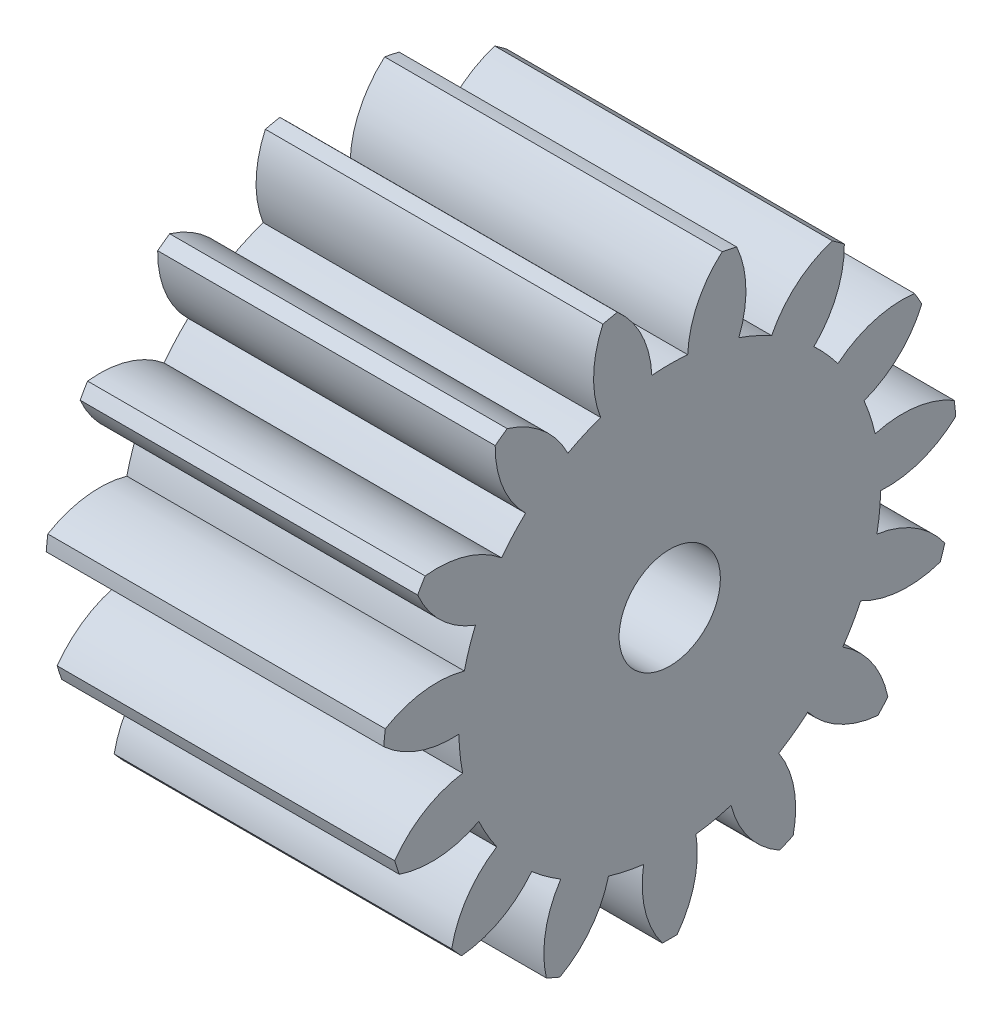
SolidWorks part; units mm, degrees
ref_plane "Plane1" through (0, 0, 0) normal (0, 0, 1) x (1, 0, 0)
ref_plane "Plane2" through (0, 0, 0) normal (0, 1, 0) x (1, 0, 0)
ref_plane "Plane3" through (0, 0, 0) normal (1, 0, 0) x (0, 0, -1)
sketch "HoldingSke" plane through (0, 0, 0) normal (0, 1, 0) x (1, 0, 0)
  line L0 (0, 0) -> (0.9659, -0.2588)
  line L1 (-15, 0) -> (100, 0) construction
  line L2 (0, 0) -> (-2.1039, 2.3779)
  line L3 (0, 0) -> (-11.863, 4.5341)
  line L4 (0, 0) -> (8.3417, 2.2352)
  line L5 (0, 0) -> (-46.8476, -17.4728)
  line L6 (0, 0) -> (-9.9476, -6.7116)
  line L7 (-2.1039, 2.3779) -> (8.6586, 51.2059)
  line L8 (-76.2, 54.61) -> (-76.1, 54.61)
  line L9 (-71.009, 38.7566) -> (-53.1078, 45.2721)
  line L10 (-76.2, 71.12) -> (104.1128, 71.12)
  line L11 (0, 0) -> (-12, 0)
  line L12 (-76.2, 101.6) -> (-76.162, 101.6)
  line L13 (24.9733, 27.94) -> (52.9518, 28.4284)
  line L14 (24.9733, 27.94) -> (24.9743, 27.94)
  line L15 (24.9733, 27.94) -> (100.4006, 29.5858)
  line L16 (-63.627, -1) -> (-12.827, -1)
  circle A0 centre (0, 0) radius 0.4
  circle A1 centre (0, 0) radius 6.249
  circle A2 centre (0, 0) radius 37.5
  circle A3 centre (0, 0) radius 0.4
  dimension "MHD" = 12.498
  dimension "Hub_dia" = 75
  dimension "Bore" = 0.8
  dimension "MBD" = 0.8
  dimension "Num_teeth" = 15
  dimension "Pitch" = 1
  dimension "Overall_len" = 50
  dimension "Show_teeth" = 15
  dimension "Thickness" = 12
  dimension "OAL" = 50.0001
  dimension "T_dim" = 0.1
  dimension "Ap" = 20
  dimension "H" = 19.05
  dimension "Pitch_radius" = 180.3128
  dimension "Width" = 12
  dimension "Backlash" = 0.038
  dimension "Addendum_fac" = 1
  dimension "Dedendum_fac" = 1.25
  dimension "Clearance_fac" = 0.25
  dimension "Dedendum_add" = 0.001
  dimension "Module" = 1
sketch "BasProSke" plane through (0, 0, 0) normal (0, 1, 0) x (1, 0, 0)
  line L0 (-10, 0) -> (60, 0) construction
  line L1 (0, 0) -> (0, 8.5)
  line L2 (0, 0) -> (10, 0)
  line L3 (10, 0) -> (10, 8.5)
  line L4 (10, 8.5) -> (0, 8.5)
  dimension "Thickness" = 10
  dimension "Diameter" = 17
revolve "Base-Revolve" add sketch "BasProSke" angle 360 about L0
sketch "TooCutSke" plane through (0, 0, 0) normal (1, 0, 0) x (0, 0, -1)
  line L1 (0, 0) -> (0, 107) construction
  line L2 (0, 0) -> (-0.8504, 7.4516) construction
  line L3 (0, 0) -> (-3.1044, 14.6049) construction
  line L4 (-0.8504, 7.4516) -> (-1.5522, 7.3025) construction
  arc A0 (0.5316, 6.2263) -> (-0.5316, 6.2263) centre (0, 0) ccw
  arc A1 (1.5766, 8.3784) -> (-1.5766, 8.3784) centre (0, 0) ccw
  circle A2 centre (0, 0) radius 7.5 construction
  circle A3 centre (0, 0) radius 7.0477 construction
  arc A4 (-0.5316, 6.2263) -> (-1.5766, 8.3784) centre (-3.5289, 6.1005) ccw
  arc A5 (1.5766, 8.3784) -> (0.5316, 6.2263) centre (3.5289, 6.1005) ccw
  dimension "Root_dia" = 12.498
  dimension "Overcut_dia" = 17.0508
  dimension "Pitch_dia" = 15
  dimension "Base_dia" = 14.0954
  dimension "Flank_rad" = 3
  dimension "Half_ang" = 12
  dimension "Half_CT" = 0.7175
extrude "ToothCut" cut sketch "TooCutSke" along normal through all
fillet "Breaks" [suppressed] radius 0.02
fillet "RootFillets" [suppressed] radius 0.251
pattern_circular "TeethCuts" count 15 every 24 about axis through (-10, 0, 0) along (1, 0, 0) of "ToothCut", "RootFillets", "Breaks"
sketch "HubNeaOneSke" plane through (0, 0, 0) normal (-1, 0, 0) x (0, 0, 1)
  circle A0 centre (0, 0) radius 6.249
  dimension "Diameter" = 12.498
extrude "HubNearOne" [suppressed] add sketch "HubNeaOneSke" along normal blind 40.0001
sketch "HubNeaBotSke" plane through (0, 0, 0) normal (-1, 0, 0) x (0, 0, 1)
  circle A0 centre (0, 0) radius 6.249
  dimension "Diameter" = 12.498
extrude "HubNearBoth" [suppressed] add sketch "HubNeaBotSke" along normal blind 20
ref_plane "FarPln" through (10, 0, 0) normal (1, 0, 0) x (0, 0, -1)
sketch "HubFarSke" plane through (10, 0, 0) normal (1, 0, 0) x (0, 0, -1)
  circle A0 centre (0, 0) radius 6.249
  dimension "Diameter" = 12.498
extrude "HubFar" [suppressed] add sketch "HubFarSke" along normal blind 20
sketch "BorSke" plane through (0, 0, 0) normal (1, 0, 0) x (0, 0, -1)
  circle A0 centre (0, 0) radius 0.4
  dimension "Diameter" = 0.8
extrude "Bore" cut sketch "BorSke" along normal mid plane 100.0001
sketch "KeySke" plane through (0, 0, 0) normal (1, 0, 0) x (0, 0, -1)
  line L0 (-0.05, 0) -> (-0.05, 0.5)
  line L1 (-0.05, 0.5) -> (0.05, 0.5)
  line L2 (0.05, 0.5) -> (0.05, 0)
  line L3 (0, 0) -> (0, 34) construction
  line L4 (-0.05, 0) -> (0.05, 0)
  dimension "Offset" = 0.5
  dimension "Width" = 0.1
extrude "Keyway" [suppressed] cut sketch "KeySke" along normal mid plane 100.0001
pattern_circular "Keyway2" [suppressed] count 2 every 90 about axis through (-10, 0, 0) along (1, 0, 0)
sketch "Sketch1" plane through (10, 0, 0) normal (1, 0, 0) x (0, 0, -1)
  circle A0 centre (0, 0) radius 1.5
  dimension "D1" = 3
extrude "Cut-Extrude1" cut sketch "Sketch1" against normal up to next
sketch "Sketch2" plane through (10, 0, 0) normal (1, 0, 0) x (0, 0, -1)
  circle A0 centre (0, 0) radius 7.3745 construction
equation "' \"Module@HoldingSke\" = 6.35"
equation "' \"Num_teeth@HoldingSke\" = 12"
equation "' \"Ap@HoldingSke\" =  20"
equation "' \"Ap@HoldingSke\" = 20"
equation "' \"Width@HoldingSke\" = 0.5 * 25.4"
equation "' \"Hub_dia@HoldingSke\"= 1 * 25.4"
equation "' \"Hub_dia@HoldingSke\" = 1 * 25.4"
equation "' \"Overall_len@HoldingSke\" = 1.0 * 25.4"
equation "' \"Bore@HoldingSke\" = 0.75 * 25.4"
equation "' \"T_dim@HoldingSke\" = 0.1 * 25.4"
equation "' \"Width@KeySke\" = 0.25 * 25.4"
equation "' \"Show_teeth@HoldingSke\" = 13"
equation "' \"Backlash@HoldingSke\" = 0.009 * 25.4"
equation "' \"Addendum_fac@HoldingSke\" = 1.0"
equation "' \"Dedendum_fac@HoldingSke\" = 1.25"
equation "' \"Dedendum_add@HoldingSke\" = 0.00005 * 25.4"
equation "' \"Clearance_fac@HoldingSke\" = 0.25"
equation "\"Pitch@HoldingSke\" = 1 / \"Module@HoldingSke\""
equation "\"Overcut_dia@TooCutSke\" = (\"Num_teeth@HoldingSke\" + 2 * \"Addendum_fac@HoldingSke\") / \"Pitch@HoldingSke\" + 0.002 * 25.4"
equation "\"Pitch_dia@TooCutSke\" = \"Num_teeth@HoldingSke\" / \"Pitch@HoldingSke\""
equation "\"Base_dia@TooCutSke\" = \"Num_teeth@HoldingSke\" / \"Pitch@HoldingSke\" * cos((\"Ap@HoldingSke\"  * 3.14159265 / 180))"
equation "\"Root_dia@TooCutSke\" = (\"Num_teeth@HoldingSke\" + 2) / \"Pitch@HoldingSke\" - 2 * (\"Addendum_fac@HoldingSke\" + \"Dedendum_fac@HoldingSke\") / \"Pitch@HoldingSke\" - \"Dedendum_add@HoldingSke\" * 2"
equation "\"Half_ang@TooCutSke\" = 180 / \"Num_teeth@HoldingSke\""
equation "\"Half_CT@TooCutSke\" = \"Num_teeth@HoldingSke\" / \"Pitch@HoldingSke\" * sin((3.14159265 / 2 / \"Num_teeth@HoldingSke\")) / 2 - 7 * \"Backlash@HoldingSke\" / 4"
equation "\"Flank_rad@TooCutSke\" = \"Num_teeth@HoldingSke\" / \"Pitch@HoldingSke\" / 5"
equation "\"Radius@RootFillets\" = \"Clearance_fac@HoldingSke\" / \"Pitch@HoldingSke\" + \"Dedendum_add@HoldingSke\""
equation "\"Break_rad@Breaks\" = 0.02 / \"Pitch@HoldingSke\""
equation "\"Thickness@HoldingSke\" = \"Width@HoldingSke\""
equation "\"OAL@HoldingSke\" = \"Thickness@HoldingSke\""
equation "\"MHD@HoldingSke\" = (\"Num_teeth@HoldingSke\" + 2) / \"Pitch@HoldingSke\" - 2 * (\"Addendum_fac@HoldingSke\" + \"Dedendum_fac@HoldingSke\")  / \"Pitch@HoldingSke\" - \"Dedendum_add@HoldingSke\" * 2"
equation "\"MBD@HoldingSke\" = (\"Num_teeth@HoldingSke\" + 2) / \"Pitch@HoldingSke\" - 2 * (\"Addendum_fac@HoldingSke\" + \"Dedendum_fac@HoldingSke\")  / \"Pitch@HoldingSke\" - \"Dedendum_add@HoldingSke\" * 2 - 0.002 * 25.4"
equation "\"MHD@HoldingSke\" = ((sgn( \"MHD@HoldingSke\" - \"Hub_dia@HoldingSke\" )-1)*( \"MHD@HoldingSke\" - \"Hub_dia@HoldingSke\" ))/-2+ \"Hub_dia@HoldingSke\""
equation "\"MBD@HoldingSke\" = ((sgn( \"MBD@HoldingSke\" - \"Bore@HoldingSke\" )-1)*( \"MBD@HoldingSke\" - \"Bore@HoldingSke\" ))/-2+ \"Bore@HoldingSke\""
equation "\"OAL@HoldingSke\" = ((sgn( \"OAL@HoldingSke\" - \"Overall_len@HoldingSke\" )+1)*( \"OAL@HoldingSke\" - \"Overall_len@HoldingSke\" ))/2 + \"Overall_len@HoldingSke\" + 0.000002 * 25.4"
equation "\"Num_teeth@TeethCuts\" = int( \"Show_teeth@HoldingSke\" ) + 1"
equation "\"Num_teeth@TeethCuts\" = ((sgn( \"Num_teeth@TeethCuts\" - \"Num_teeth@HoldingSke\" )-1)*( \"Num_teeth@TeethCuts\" - \"Num_teeth@HoldingSke\" ))/-2+ \"Num_teeth@HoldingSke\""
equation "\"Num_teeth@TeethCuts\" = ((sgn( \"Num_teeth@TeethCuts\" - 2.0)+1)*( \"Num_teeth@TeethCuts\" - 2.0))/2 +2.0"
equation "\"Angle@TeethCuts\" = 360.0 / \"Num_teeth@HoldingSke\""
equation "\"Diameter@BasProSke\" = (\"Num_teeth@HoldingSke\" + 2 * \"Addendum_fac@HoldingSke\") / \"Pitch@HoldingSke\""
equation "' \"Fillet_rad@BasProSke\" =  \"Thickness@HoldingSke\" * 0.05"
equation "' \"Fillet_rad@BasProSke\" = \"Thickness@HoldingSke\" * 0.05"
equation "\"MHD@HoldingSke\" = ((sgn( \"MHD@HoldingSke\" - \"Root_dia@TooCutSke\" )-1)*( \"MHD@HoldingSke\" - \"Root_dia@TooCutSke\" ))/-2+ \"Root_dia@TooCutSke\""
equation "\"Diameter@HubNeaOneSke\" = \"MHD@HoldingSke\""
equation "\"Length@HubNearOne\" = \"OAL@HoldingSke\" - \"Thickness@BasProSke\""
equation "\"Diameter@HubNeaBotSke\" = \"MHD@HoldingSke\""
equation "\"Length@HubNearBoth\" = ( \"OAL@HoldingSke\" - \"Thickness@BasProSke\" ) / 2.0"
equation "\"Thickness@FarPln\" = \"Thickness@BasProSke\""
equation "\"Diameter@HubFarSke\" = \"MHD@HoldingSke\""
equation "\"Length@HubFar\" = ( \"OAL@HoldingSke\" - \"Thickness@BasProSke\" ) / 2.0"
equation "\"Diameter@BorSke\" = \"MBD@HoldingSke\""
equation "\"D1@Bore\" = \"OAL@HoldingSke\" * 2.0"
equation "\"D1@Keyway\" = \"OAL@HoldingSke\" * 2.0"
equation "\"Offset@KeySke\" = \"T_dim@HoldingSke\" + \"MBD@HoldingSke\" / 2.0"
